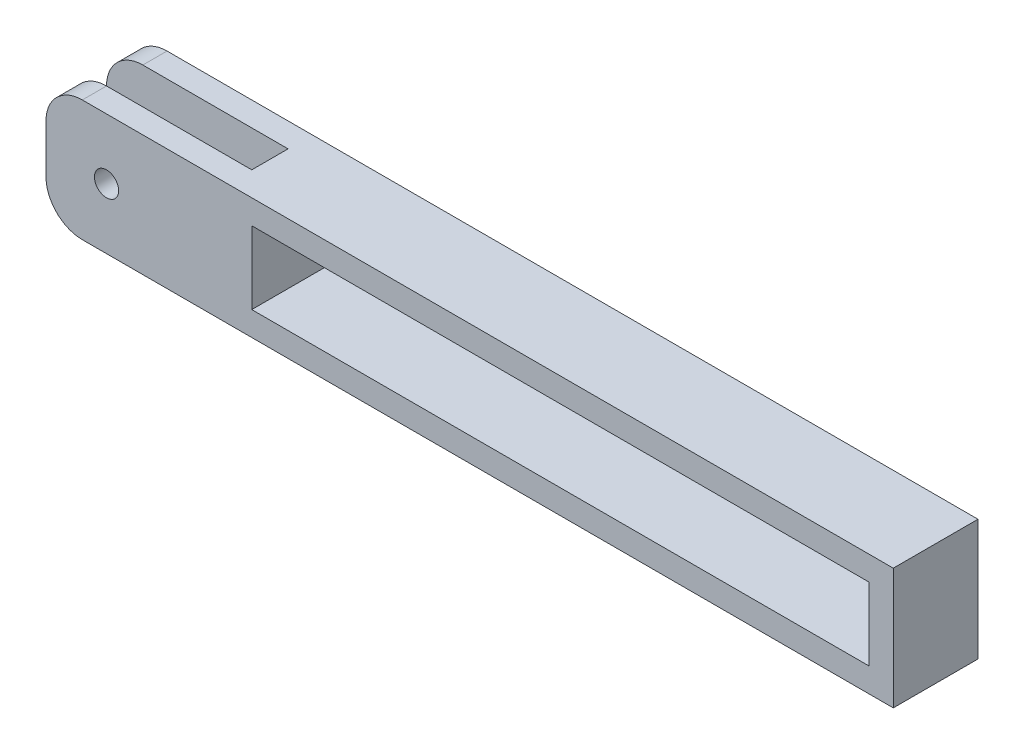
SolidWorks part; units mm, degrees
ref_plane "Front" through (0, 0, 0) normal (0, 0, 1) x (1, 0, 0)
ref_plane "Top" through (0, 0, 0) normal (0, 1, 0) x (1, 0, 0)
ref_plane "Right" through (0, 0, 0) normal (1, 0, 0) x (0, 0, -1)
sketch "Sketch1" plane through (0, 0, 0) normal (0, 0, 1) x (1, 0, 0)
  line L1 (-10, 25) -> (325, 25)
  line L2 (-25, 10) -> (-25, -10)
  line L3 (-10, -25) -> (325, -25)
  line L4 (325, 25) -> (325, -25)
  arc A1 (-10, -25) -> (-25, -10) centre (-10, -10) cw
  arc A2 (-10, 25) -> (-25, 10) centre (-10, 10) ccw
  dimension "D6" = 15
  dimension "D1" = 50
  dimension "D2" = 350
  dimension "D3" = 25
  dimension "D4" = 25
extrude "Extrude1" add sketch "Sketch1" along normal mid plane 35
sketch "Sketch2" plane through (0, 25, 0) normal (0, 1, 0) x (-1, 0, 0)
  line L0 (25, 17.5) -> (25, -17.5) construction
  line L1 (25, -7.5) -> (-50, -7.5)
  line L2 (25, -7.5) -> (25, 7.5)
  line L3 (25, 7.5) -> (-50, 7.5)
  line L4 (-50, -7.5) -> (-50, 7.5)
  point P6 (25, 0)
  dimension "D1" = 75
  dimension "D2" = 15
extrude "Cut-Extrude1" cut sketch "Sketch2" against normal through all
sketch "Sketch3" plane through (0, 0, 0) normal (0, 0, 1) x (1, 0, 0)
  circle A0 centre (0, 0) radius 5
  dimension "D1" = 10
extrude "Cut-Extrude2" cut sketch "Sketch3" against normal through all and the other way through all
sketch "Sketch4" plane through (0, 0, 0) normal (0, 0, 1) x (1, 0, 0)
  line L2 (60, -25) -> (60, 25)
  line L3 (60, -15) -> (60, 15)
  line L9 (-10, -15) -> (315, -15)
  line L10 (315, -15) -> (315, 15)
  line L11 (315, 15) -> (-10, 15)
  line L12 (60, -15) -> (315, -15)
  line L13 (315, -15) -> (315, 15)
  line L14 (315, 15) -> (60, 15)
  dimension "D1" = 10
  dimension "D2" = 10
extrude "Cut-Extrude3" cut sketch "Sketch4" against normal through all and the other way through all
